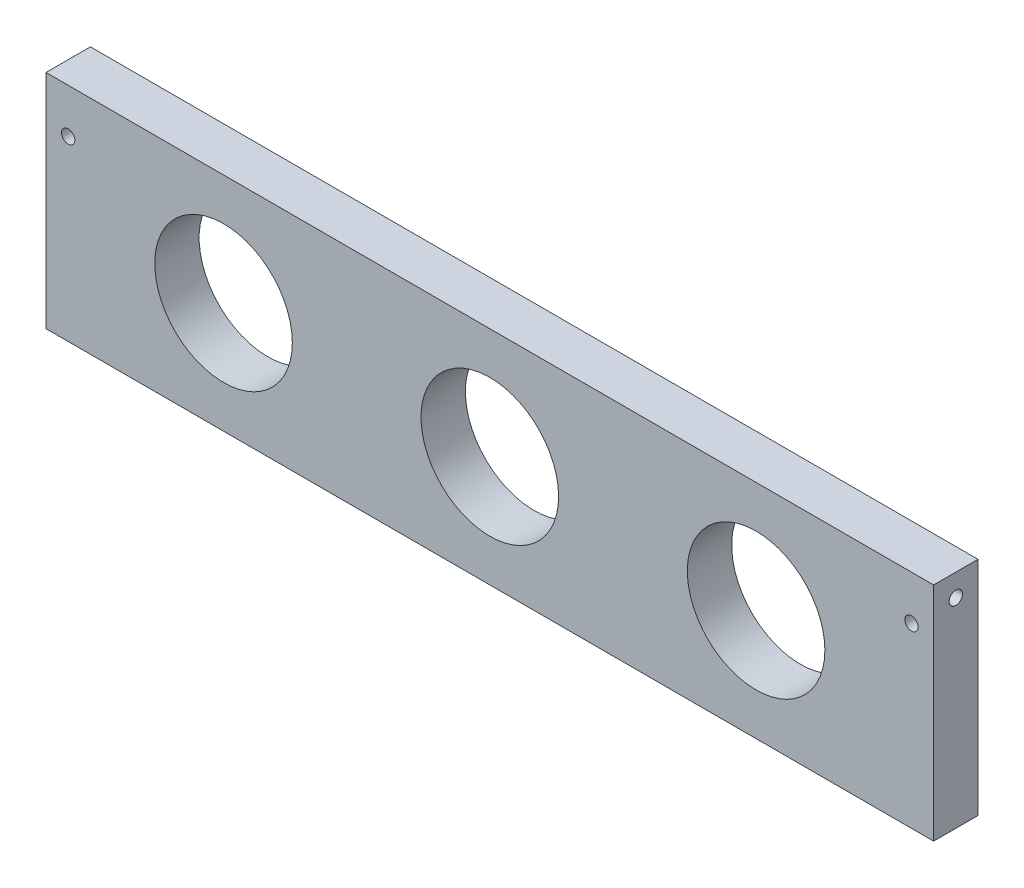
SolidWorks part; units mm, degrees
material "Perspex (TM) GS Acrylic Cast Sheet"
ref_plane "Front Plane" through (0, 0, 0) normal (0, 0, 1) x (1, 0, 0)
ref_plane "Top Plane" through (0, 0, 0) normal (0, 1, 0) x (1, 0, 0)
ref_plane "Right Plane" through (0, 0, 0) normal (1, 0, 0) x (0, 0, -1)
sketch "Sketch1" plane through (0, 0, 0) normal (0, 0, 1) x (1, 0, 0)
  line L1 (-100, 25) -> (100, 25)
  line L2 (-100, 25) -> (-100, -25)
  line L3 (-100, -25) -> (100, -25)
  line L4 (100, 25) -> (100, -25)
  line L5 (-100, 25) -> (100, -25) construction
  line L6 (-100, -25) -> (100, 25) construction
  circle A0 centre (0, 0) radius 15.5
  circle A1 centre (60, 0) radius 15.5
  circle A2 centre (-60, 0) radius 15.5
  circle A3 centre (95, 15) radius 1.5
  circle A4 centre (-95, 15) radius 1.5
  point P0 (0, 0)
  dimension "D3" = 31
  dimension "D4" = 60
  dimension "D5" = 60
  dimension "D6" = 3
  dimension "D7" = 10
  dimension "D8" = 5
  dimension "D9" = 5
  dimension "D1" = 200
  dimension "D2" = 50
extrude "Boss-Extrude1" add sketch "Sketch1" along normal blind 10
sketch "Sketch2" plane through (0, -25, 0) normal (0, -1, 0) x (1, 0, 0)
  line L0 (-100, 10) -> (100, 10) construction
  line L1 (-100, 10) -> (-100, 0) construction
  line L2 (100, 10) -> (100, 0) construction
  circle A0 centre (-95, 5) radius 2.5
  circle A2 centre (95, 5) radius 2.5
  dimension "D1" = 5
  dimension "D2" = 5
  dimension "D3" = 5
  dimension "D4" = 5
extrude "Cut-Extrude1" cut sketch "Sketch2" against normal blind 10
sketch "Sketch3" plane through (100, 0, 0) normal (1, 0, 0) x (0, 0, -1)
  line L0 (0, -25) -> (0, 25) construction
  line L1 (-10, 25) -> (0, 25) construction
  circle A0 centre (-5, 20) radius 1.5
  dimension "D1" = 3
  dimension "D2" = 5
  dimension "D3" = 5
extrude "Cut-Extrude2" cut sketch "Sketch3" against normal blind 200
